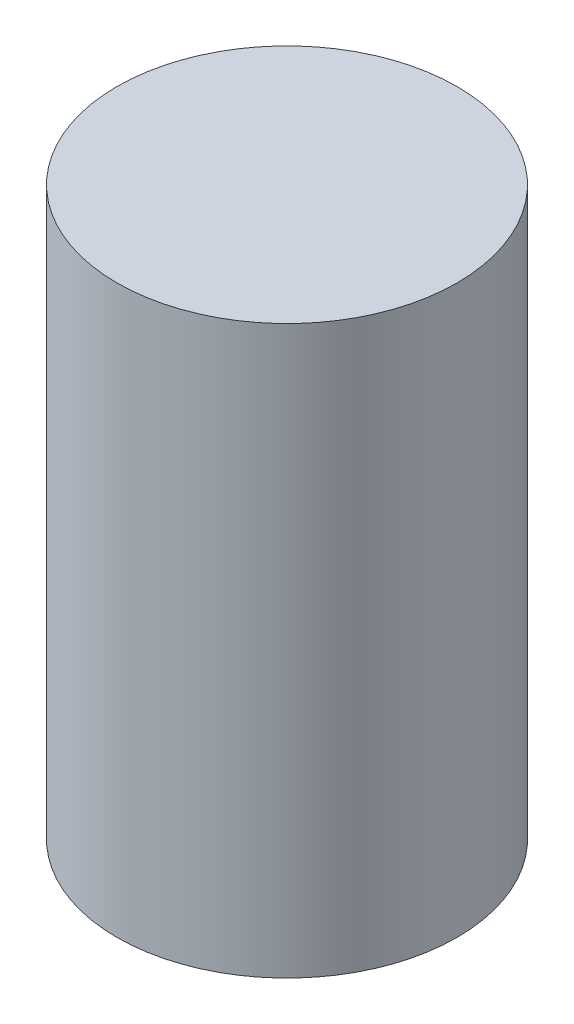
SolidWorks part; units mm, degrees
ref_plane "Front Plane" through (0, 0, 0) normal (0, 0, 1) x (1, 0, 0)
ref_plane "Top Plane" through (0, 0, 0) normal (0, 1, 0) x (1, 0, 0)
ref_plane "Right Plane" through (0, 0, 0) normal (1, 0, 0) x (0, 0, -1)
sketch "Sketch1" plane through (0, 0, 0) normal (0, 1, 0) x (1, 0, 0)
  circle A0 centre (0, 0) radius 3
extrude "Boss-Extrude1" add sketch "Sketch1" along normal blind 10
